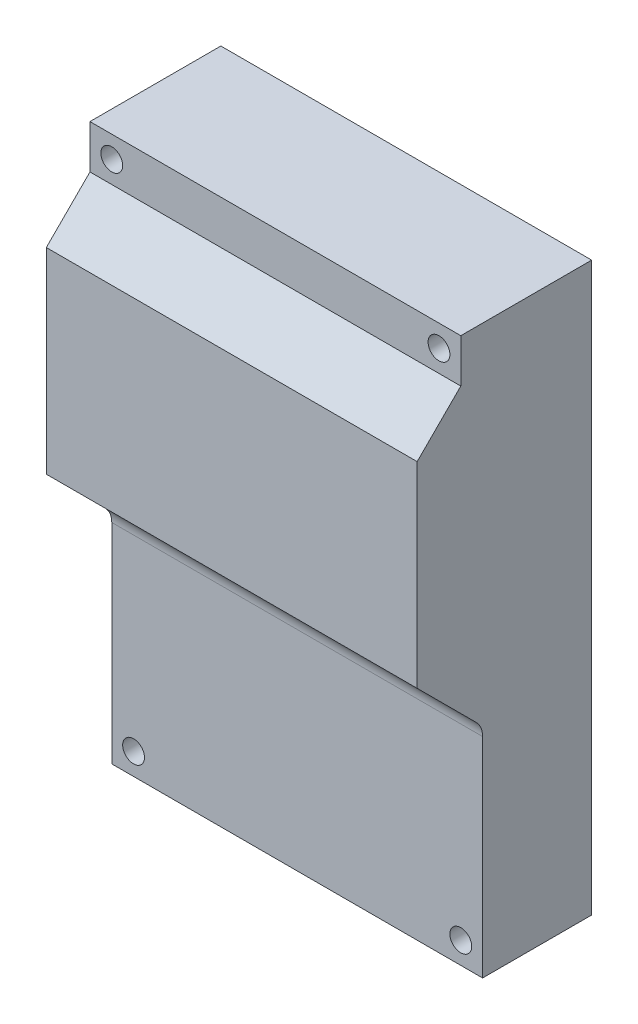
SolidWorks part; units mm, degrees
material "Alluminio Bronzo"
ref_plane "Piano frontale" through (0, 0, 0) normal (0, 0, 1) x (1, 0, 0)
ref_plane "Piano superiore" through (0, 0, 0) normal (0, 1, 0) x (1, 0, 0)
ref_plane "Piano destro" through (0, 0, 0) normal (1, 0, 0) x (0, 0, -1)
other "Centro di massa"
sketch "Schizzo1" plane through (0, 0, 0) normal (0, 0, 1) x (1, 0, 0)
  line L0 (-37.5, 60) -> (37.5, 60) construction
  line L1 (-42.5, 65) -> (42.5, 65)
  line L2 (-42.5, 65) -> (-42.5, -65)
  line L3 (-42.5, -65) -> (42.5, -65)
  line L4 (42.5, 65) -> (42.5, -65)
  line L5 (-42.5, 65) -> (42.5, -65) construction
  line L6 (-42.5, -65) -> (42.5, 65) construction
  line L7 (37.5, 60) -> (37.5, -60) construction
  line L8 (-37.5, -60) -> (37.5, -60) construction
  line L9 (-37.5, 60) -> (-37.5, -60) construction
  circle A0 centre (-37.5, 60) radius 2.5
  circle A1 centre (37.5, 60) radius 2.5
  circle A2 centre (37.5, -60) radius 2.5
  circle A3 centre (-37.5, -60) radius 2.5
  point P0 (0, 0)
  dimension "D4" = 5
  dimension "D1" = 85
  dimension "D2" = 130
  dimension "D5" = 2
  dimension "D3" = 5
  dimension "D6" = 2
extrude "Estrusione-Estrusione1" add sketch "Schizzo1" along normal blind 40
sketch "Schizzo2" plane through (42.5, 0, 0) normal (1, 0, 0) x (0, 0, -1)
  line L0 (-40, 65) -> (-30, 65)
  line L1 (-40, 65) -> (0, 65) construction
  line L2 (-30, 65) -> (-30, 55)
  line L3 (-30, 55) -> (-40, 45)
  line L4 (-40, -65) -> (-40, 65) construction
  line L5 (-40, 45) -> (-40, 65)
  line L6 (-40, 0) -> (-40, -65)
  line L7 (-40, -65) -> (-25, -65)
  line L8 (-40, -65) -> (0, -65) construction
  line L9 (-25, -65) -> (-25, -17.0711)
  line L10 (-26.4645, -13.5355) -> (-40, 0)
  arc A0 (-25, -17.0711) -> (-26.4645, -13.5355) centre (-30, -17.0711) ccw
  dimension "D6" = 5
  dimension "D1" = 10
  dimension "D2" = 135
  dimension "D3" = 20
  dimension "D4" = 135
  dimension "D5" = 15
extrude "Taglio-Estrusione1" cut sketch "Schizzo2" against normal through all
other "Punto di riferimento centro di massa1"
